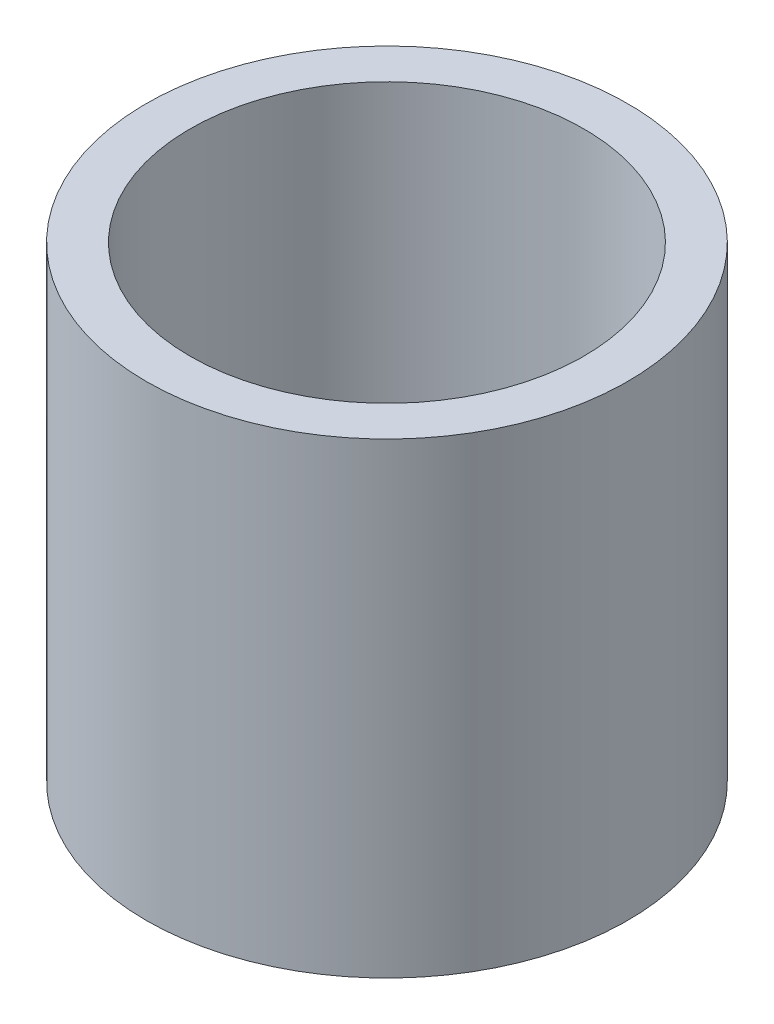
SolidWorks part; units mm, degrees
ref_plane "Front Plane" through (0, 0, 0) normal (0, 0, 1) x (1, 0, 0)
ref_plane "Top Plane" through (0, 0, 0) normal (0, 1, 0) x (1, 0, 0)
ref_plane "Right Plane" through (0, 0, 0) normal (1, 0, 0) x (0, 0, -1)
sketch "Sketch2" plane through (0, 0, 0) normal (0, 0, 1) x (1, 0, 0)
  line L0 (42.8625, 0) -> (42.8625, -101.6)
  line L1 (42.8625, -101.6) -> (52.3875, -101.6)
  line L2 (52.3875, -101.6) -> (52.3875, 0)
  line L3 (52.3875, 0) -> (42.8625, 0)
  dimension "D1" = 101.6
  dimension "D2" = 9.525
  dimension "D3" = 52.3875
ref_axis "Axis1" through (0, 2.54, 0) along (0, -1, 0)
revolve "Revolve1" add sketch "Sketch2" angle 360 about axis through (0, 2.54, 0) along (0, -1, 0)
equation "\"Height\"=4"
equation "\"Radius\"=0.375"
equation "\"D1@Sketch2\"=\"Height\""
equation "\"D2@Sketch2\"=\"Radius\""
